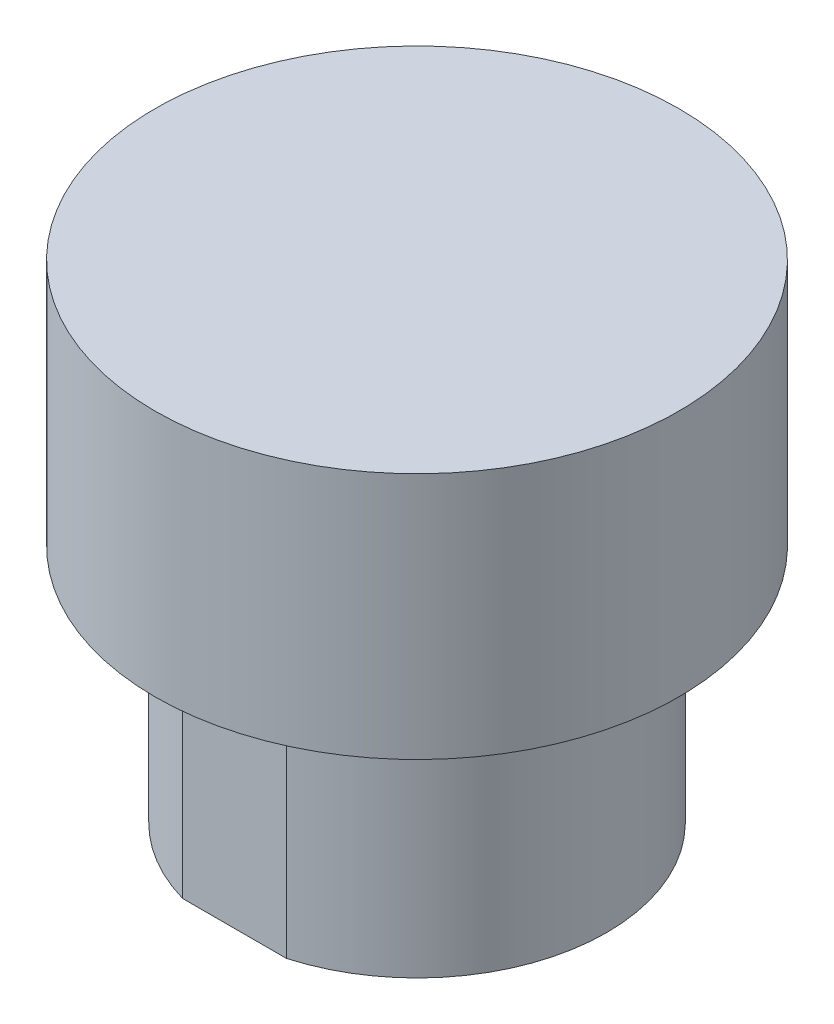
SolidWorks part; units mm, degrees
ref_plane "Front Plane" through (0, 0, 0) normal (0, 0, 1) x (1, 0, 0)
ref_plane "Top Plane" through (0, 0, 0) normal (0, 1, 0) x (1, 0, 0)
ref_plane "Right Plane" through (0, 0, 0) normal (1, 0, 0) x (0, 0, -1)
sketch "Sketch1" plane through (0, 0, 0) normal (0, 1, 0) x (1, 0, 0)
  line L0 (-2.8705, 10.1) -> (2.8705, 10.1)
  line L1 (2.8705, 10.1) -> (2.8705, -10.1) construction
  line L2 (2.8705, -10.1) -> (-2.8705, -10.1)
  circle A0 centre (0, 0) radius 10.5
  dimension "D1" = 21
  dimension "D2" = 20.2
extrude "Boss-Extrude1" add sketch "Sketch1" along normal blind 13.3 contours L1 L0 A0 L2 | A0 L1
sketch "Sketch2" plane through (0, 13.3, 0) normal (0, 1, 0) x (1, 0, 0)
  circle A0 centre (0, 0) radius 14.5
  dimension "D1" = 29
extrude "Boss-Extrude2" add sketch "Sketch2" along normal blind 13.7
